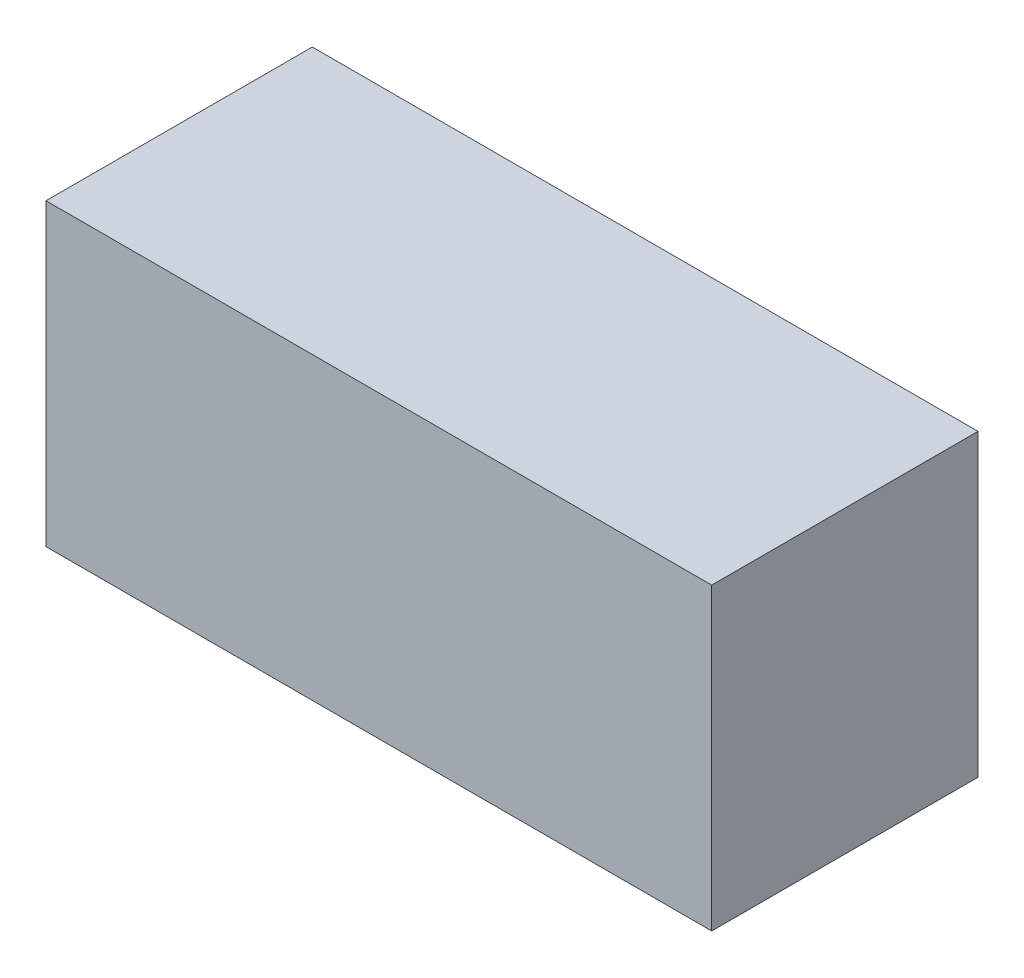
SolidWorks part; units mm, degrees
material "1060 Alloy"
ref_plane "Front" through (0, 0, 0) normal (0, 0, 1) x (1, 0, 0)
ref_plane "Top" through (0, 0, 0) normal (0, 1, 0) x (1, 0, 0)
ref_plane "Right" through (0, 0, 0) normal (1, 0, 0) x (0, 0, -1)
sketch "Sketch1" plane through (0, 0, 0) normal (0, 1, 0) x (1, 0, 0)
  line L1 (-127, 50.8) -> (127, 50.8)
  line L2 (-127, 50.8) -> (-127, -50.8)
  line L3 (-127, -50.8) -> (127, -50.8)
  line L4 (127, 50.8) -> (127, -50.8)
  line L5 (-127, 50.8) -> (127, -50.8) construction
  line L6 (-127, -50.8) -> (127, 50.8) construction
  point P0 (0, 0)
  dimension "D1" = 101.6
  dimension "D2" = 254
extrude "Boss-Extrude1" add sketch "Sketch1" along normal blind 6.35
sketch "Sketch5" plane through (0, 6.35, 0) normal (0, 1, 0) x (1, 0, 0)
  line L11 (-127, 50.8) -> (127, 50.8)
  line L12 (-127, 50.8) -> (-127, -50.8)
  line L13 (-127, -50.8) -> (127, -50.8)
  line L14 (120.65, -44.45) -> (120.65, 44.45)
  line L15 (-120.65, -44.45) -> (120.65, -44.45)
  line L16 (-120.65, 44.45) -> (-120.65, -44.45)
  line L17 (120.65, 44.45) -> (-120.65, 44.45)
  line L18 (120.65, -44.45) -> (120.65, 44.45)
  line L19 (-120.65, -44.45) -> (120.65, -44.45)
  line L20 (-120.65, 44.45) -> (-120.65, -44.45)
  line L21 (120.65, 44.45) -> (-120.65, 44.45)
  line L22 (127, 50.8) -> (127, -50.8)
  dimension "D1" = 6.35
extrude "Boss-Extrude4" add sketch "Sketch5" along normal blind 101.6
sketch "Sketch6" plane through (0, 107.95, 0) normal (0, 1, 0) x (1, 0, 0)
  line L1 (-127, -50.8) -> (127, -50.8)
  line L2 (-127, -50.8) -> (-127, 50.8)
  line L3 (-127, 50.8) -> (127, 50.8)
  line L4 (127, -50.8) -> (127, 50.8)
extrude "Boss-Extrude5" add sketch "Sketch6" along normal blind 6.35
